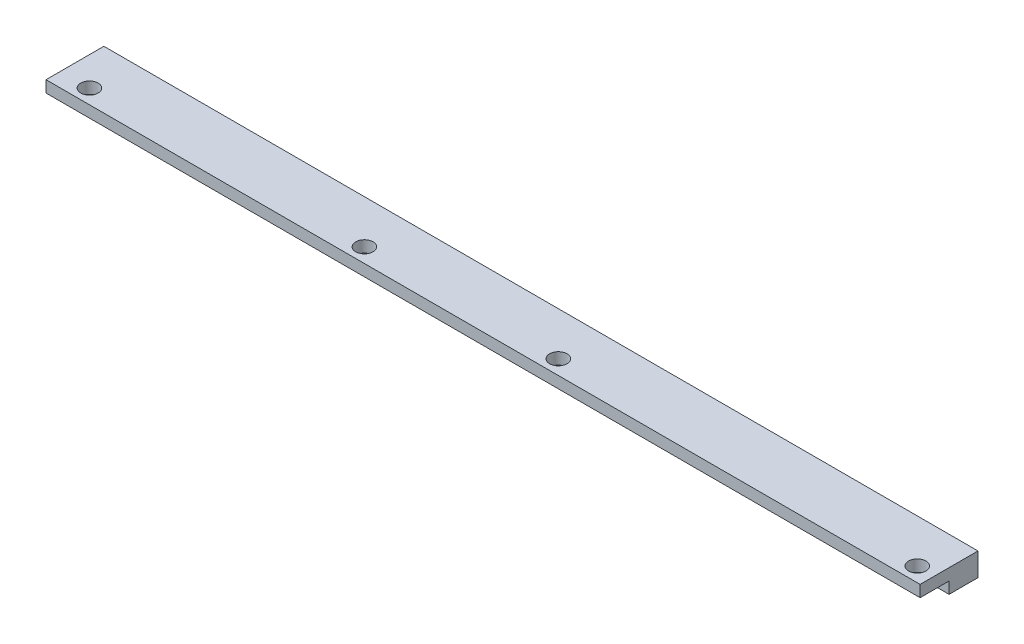
SolidWorks part; units mm, degrees
ref_plane "前视基准面" through (0, 0, 0) normal (0, 0, 1) x (1, 0, 0)
ref_plane "上视基准面" through (0, 0, 0) normal (0, 1, 0) x (1, 0, 0)
ref_plane "右视基准面" through (0, 0, 0) normal (1, 0, 0) x (0, 0, -1)
other "Configuration Table"
sketch "草图1" plane through (0, 0, 0) normal (0, 1, 0) x (1, 0, 0)
  line L1 (0, -5) -> (151, -5)
  line L2 (0, -5) -> (0, 0)
  line L3 (0, 0) -> (151, 0)
  line L4 (151, -5) -> (151, 0)
  circle A2 centre (5, -2.5) radius 1.5
  circle A3 centre (52.5, -2.5) radius 1.5
  circle A4 centre (86, -2.5) radius 1.5
  circle A5 centre (148, -2.5) radius 1.5
  point P9 (0, -2.5)
  dimension "D1" = 3
  dimension "D2" = 5
  dimension "D3" = 5
  dimension "D4" = 3
extrude "凸台-拉伸1" add sketch "草图1" along normal blind 2 contours L3 L4 L1 L2 | A2 | A3 | A4 | A5
sketch "草图2" plane through (0, 0, 0) normal (0, 1, 0) x (1, 0, 0)
  line L0 (151, -5) -> (151, 0) construction
  line L1 (0, 5) -> (151, 5)
  line L2 (0, 5) -> (0, 0)
  line L3 (0, 0) -> (151, 0)
  line L4 (151, 5) -> (151, 0)
  line L5 (0, 0) -> (151, 0) construction
  dimension "D1" = 5
extrude "凸台-拉伸2" add sketch "草图2" against normal blind 4 from surface at 2 starting at face at (75.5, 2, 2.5)
